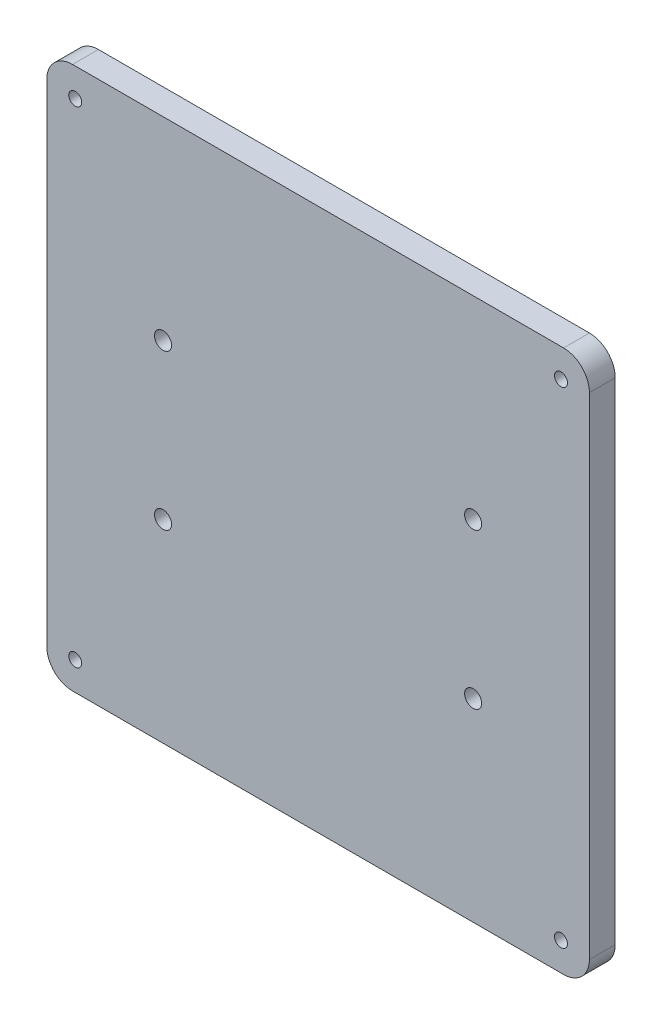
SolidWorks part; units mm, degrees
ref_plane "Plan de face" through (0, 0, 0) normal (0, 0, 1) x (1, 0, 0)
ref_plane "Plan de dessus" through (0, 0, 0) normal (0, 1, 0) x (1, 0, 0)
ref_plane "Plan de droite" through (0, 0, 0) normal (1, 0, 0) x (0, 0, -1)
sketch "Esquisse1" plane through (0, 0, 0) normal (0, 0, 1) x (1, 0, 0)
  line L0 (0, 52.5) -> (105, 52.5) construction
  line L1 (0, 0) -> (105, 0)
  line L2 (0, 0) -> (0, 105)
  line L3 (0, 105) -> (105, 105)
  line L4 (105, 0) -> (105, 105)
  line L5 (52.5, 105) -> (52.5, 0) construction
  circle A0 centre (5.5, 5.5) radius 1.25
  circle A1 centre (99.5, 5.5) radius 1.25
  circle A2 centre (99.5, 99.5) radius 1.25
  circle A3 centre (5.5, 99.5) radius 1.25
  circle A4 centre (22.5, 67.5) radius 1.65
  circle A5 centre (22.5, 37.5) radius 1.65
  circle A6 centre (82.5, 37.5) radius 1.65
  circle A7 centre (82.5, 67.5) radius 1.65
  dimension "D1" = 94
  dimension "D2" = 2.5
  dimension "D6" = 30
  dimension "D7" = 3.3
  dimension "D8" = 60
  dimension "D3" = 94
  dimension "D4" = 105
  dimension "D5" = 105
extrude "Boss.-Extru.1" add sketch "Esquisse1" along normal blind 5
fillet "Congé1" radius 5 4 edges at (0, 105, 2.5) (105, 105, 2.5) (105, 0, 2.5) (0, 0, 2.5)
